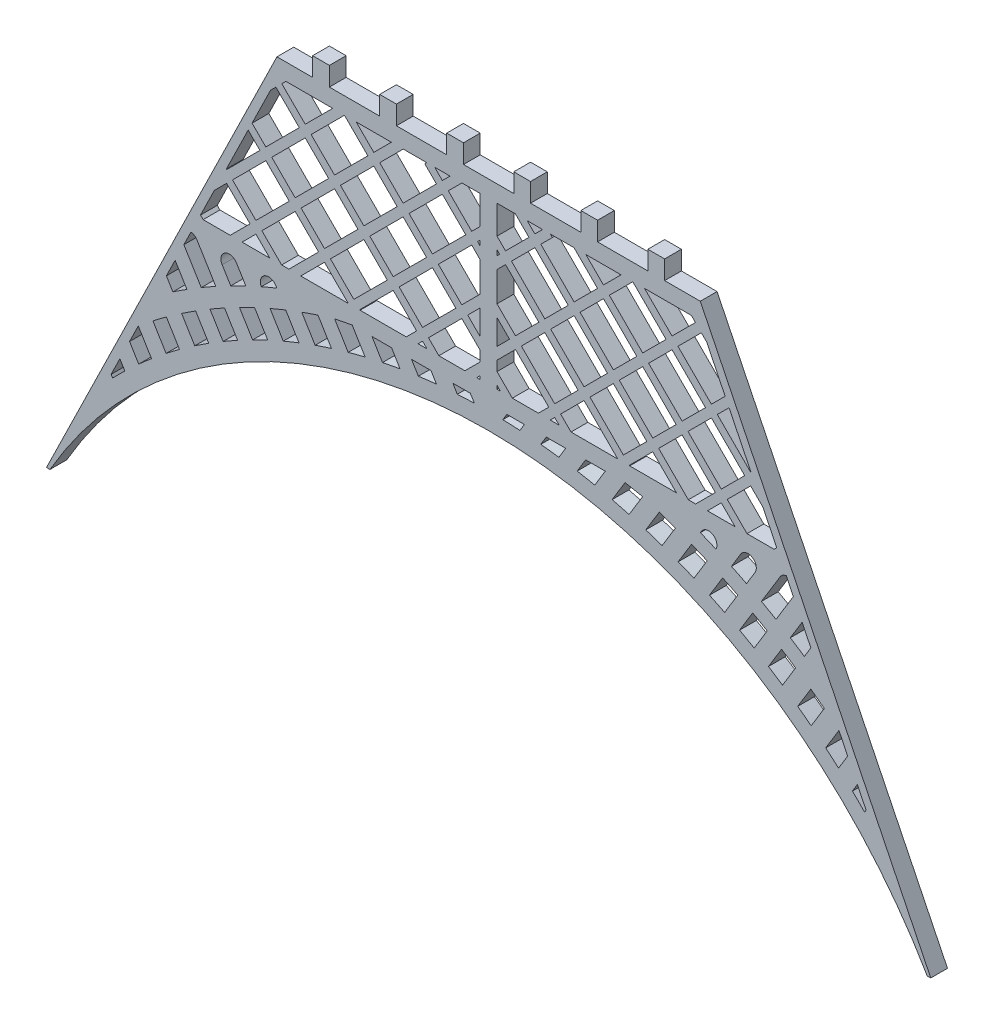
SolidWorks part; units mm, degrees
ref_plane "Front Plane" through (0, 0, 0) normal (0, 0, 1) x (1, 0, 0)
ref_plane "Top Plane" through (0, 0, 0) normal (0, 1, 0) x (1, 0, 0)
ref_plane "Right Plane" through (0, 0, 0) normal (1, 0, 0) x (0, 0, -1)
sketch "Sketch1" plane through (0, 0, 0) normal (0, 0, 1) x (1, 0, 0)
  line L1193 (183.6182, 220.7026) -> (187.8075, 224.8919)
  line L1194 (187.8075, 224.8919) -> (181.8448, 230.8547)
  line L1195 (181.8448, 230.8547) -> (180.3157, 229.3256)
  line L1196 (180.3157, 229.3256) -> (180.3157, 224.005)
  line L1197 (180.3157, 224.005) -> (183.6182, 220.7026)
  line L1198 (181.8448, 232.976) -> (186.0341, 237.1653)
  line L1199 (186.0341, 237.1653) -> (183.597, 239.6025)
  line L1200 (183.597, 239.6025) -> (180.3157, 239.6025)
  line L1201 (180.3157, 239.6025) -> (180.3157, 234.505)
  line L1202 (180.3157, 234.505) -> (181.8448, 232.976)
  line L1203 (180.9402, 210.7592) -> (180.3157, 211.3837)
  line L1204 (180.3157, 211.3837) -> (180.3157, 210.7592)
  line L1205 (180.3157, 210.7592) -> (180.9402, 210.7592)
  line L1206 (183.0615, 210.7592) -> (187.7216, 210.7592)
  line L1207 (187.7216, 210.7592) -> (189.5809, 212.6185)
  line L1208 (189.5809, 212.6185) -> (183.6182, 218.5813)
  line L1209 (183.6182, 218.5813) -> (180.3157, 215.2788)
  line L1210 (180.3157, 215.2788) -> (180.3157, 213.505)
  line L1211 (180.3157, 213.505) -> (183.0615, 210.7592)
  line L1212 (180.7841, 231.9153) -> (180.3157, 232.3837)
  line L1213 (180.3157, 232.3837) -> (180.3157, 231.4469)
  line L1214 (180.3157, 231.4469) -> (180.7841, 231.9153)
  line L1215 (182.5575, 219.6419) -> (180.3157, 221.8837)
  line L1216 (180.3157, 221.8837) -> (180.3157, 217.4002)
  line L1217 (180.3157, 217.4002) -> (182.5575, 219.6419)
  line L1218 (200.4288, 235.3919) -> (206.3916, 229.4292)
  line L1219 (206.3916, 229.4292) -> (210.5809, 233.6185)
  line L1220 (210.5809, 233.6185) -> (204.6182, 239.5813)
  line L1221 (204.6182, 239.5813) -> (200.4288, 235.3919)
  line L1222 (199.3682, 236.4526) -> (196.2183, 239.6025)
  line L1223 (196.2183, 239.6025) -> (202.5181, 239.6025)
  line L1224 (202.5181, 239.6025) -> (199.3682, 236.4526)
  line L1225 (195.1788, 230.1419) -> (201.1416, 224.1792)
  line L1226 (201.1416, 224.1792) -> (205.3309, 228.3685)
  line L1227 (205.3309, 228.3685) -> (199.3682, 234.3313)
  line L1228 (199.3682, 234.3313) -> (195.1788, 230.1419)
  line L1229 (198.3075, 235.3919) -> (194.1182, 231.2026)
  line L1230 (194.1182, 231.2026) -> (188.1554, 237.1653)
  line L1231 (188.1554, 237.1653) -> (190.241, 239.2509)
  line L1232 (190.241, 239.2509) -> (189.8895, 239.6025)
  line L1233 (189.8895, 239.6025) -> (194.097, 239.6025)
  line L1234 (194.097, 239.6025) -> (198.3075, 235.3919)
  line L1235 (187.0948, 236.1047) -> (182.9054, 231.9153)
  line L1236 (182.9054, 231.9153) -> (188.8682, 225.9526)
  line L1237 (188.8682, 225.9526) -> (193.0575, 230.1419)
  line L1238 (193.0575, 230.1419) -> (187.0948, 236.1047)
  line L1239 (189.9288, 224.8919) -> (195.8916, 218.9292)
  line L1240 (195.8916, 218.9292) -> (200.0809, 223.1185)
  line L1241 (200.0809, 223.1185) -> (194.1182, 229.0813)
  line L1242 (194.1182, 229.0813) -> (189.9288, 224.8919)
  line L1243 (215.8309, 238.8685) -> (215.097, 239.6025)
  line L1244 (215.097, 239.6025) -> (206.7183, 239.6025)
  line L1245 (206.7183, 239.6025) -> (211.6416, 234.6792)
  line L1246 (211.6416, 234.6792) -> (215.8309, 238.8685)
  line L1247 (207.4522, 228.3685) -> (213.4385, 222.3822)
  line L1248 (213.4385, 222.3822) -> (217.6279, 226.5716)
  line L1249 (217.6279, 226.5716) -> (211.6416, 232.5579)
  line L1250 (211.6416, 232.5579) -> (207.4522, 228.3685)
  line L1251 (202.2022, 223.1185) -> (208.1885, 217.1322)
  line L1252 (208.1885, 217.1322) -> (212.3779, 221.3216)
  line L1253 (212.3779, 221.3216) -> (206.3916, 227.3079)
  line L1254 (206.3916, 227.3079) -> (202.2022, 223.1185)
  line L1255 (196.9522, 217.8685) -> (202.9385, 211.8822)
  line L1256 (202.9385, 211.8822) -> (207.1279, 216.0716)
  line L1257 (207.1279, 216.0716) -> (201.1416, 222.0579)
  line L1258 (201.1416, 222.0579) -> (196.9522, 217.8685)
  line L1259 (188.8682, 223.8313) -> (184.6788, 219.6419)
  line L1260 (184.6788, 219.6419) -> (190.6416, 213.6792)
  line L1261 (190.6416, 213.6792) -> (194.8309, 217.8685)
  line L1262 (194.8309, 217.8685) -> (188.8682, 223.8313)
  line L1263 (193.5615, 210.7592) -> (201.8155, 210.7592)
  line L1264 (201.8155, 210.7592) -> (201.8779, 210.8216)
  line L1265 (201.8779, 210.8216) -> (195.8916, 216.8079)
  line L1266 (195.8916, 216.8079) -> (191.7022, 212.6185)
  line L1267 (191.7022, 212.6185) -> (193.5615, 210.7592)
  line L1268 (189.8429, 210.7592) -> (191.4402, 210.7592)
  line L1269 (191.4402, 210.7592) -> (190.6416, 211.5579)
  line L1270 (190.6416, 211.5579) -> (189.8429, 210.7592)
  line L1271 (187.0948, 238.226) -> (185.7183, 239.6025)
  line L1272 (185.7183, 239.6025) -> (188.4713, 239.6025)
  line L1273 (188.4713, 239.6025) -> (187.0948, 238.226)
  line L1274 (218.6885, 225.5109) -> (214.4992, 221.3216)
  line L1275 (214.4992, 221.3216) -> (220.4619, 215.3588)
  line L1276 (220.4619, 215.3588) -> (224.6513, 219.5482)
  line L1277 (224.6513, 219.5482) -> (218.6885, 225.5109)
  line L1278 (213.4385, 220.2609) -> (209.2492, 216.0716)
  line L1279 (209.2492, 216.0716) -> (214.5615, 210.7592)
  line L1280 (214.5615, 210.7592) -> (215.8623, 210.7592)
  line L1281 (215.8623, 210.7592) -> (219.4013, 214.2982)
  line L1282 (219.4013, 214.2982) -> (213.4385, 220.2609)
  line L1283 (217.9836, 210.7592) -> (222.9402, 210.7592)
  line L1284 (222.9402, 210.7592) -> (220.4619, 213.2375)
  line L1285 (220.4619, 213.2375) -> (217.9836, 210.7592)
  line L1286 (204.0615, 210.7592) -> (212.4402, 210.7592)
  line L1287 (212.4402, 210.7592) -> (208.1885, 215.0109)
  line L1288 (208.1885, 215.0109) -> (203.9992, 210.8216)
  line L1289 (203.9992, 210.8216) -> (204.0615, 210.7592)
  line L1290 (206.3818, 207.1538) -> (203.9493, 203.1685)
  line L1291 (200.9169, 203.9585) -> (203.2366, 207.7592)
  line L1292 (203.2366, 207.7592) -> (206.3818, 207.1538)
  line L1293 (199.7013, 207.7592) -> (197.8081, 204.6574)
  line L1294 (194.6573, 205.2536) -> (196.1866, 207.7592)
  line L1295 (196.1866, 207.7592) -> (199.7013, 207.7592)
  line L1296 (185.2265, 207.7592) -> (184.4181, 206.4348)
  line L1297 (181.3595, 206.5679) -> (182.0866, 207.7592)
  line L1298 (182.0866, 207.7592) -> (185.2265, 207.7592)
  line L1299 (212.2588, 205.232) -> (209.8641, 201.3086)
  line L1300 (206.943, 202.2809) -> (209.355, 206.2328)
  line L1301 (217.9315, 202.9754) -> (215.5634, 199.0955)
  line L1302 (212.7485, 200.242) -> (215.1285, 204.1415)
  line L1303 (223.4062, 200.3944) -> (221.0545, 196.5415)
  line L1304 (218.3427, 197.8568) -> (220.7013, 201.7212)
  line L1305 (228.6869, 197.4956) -> (226.3422, 193.654)
  line L1306 (223.7314, 195.1349) -> (226.0784, 198.9802)
  line L1307 (233.7605, 194.2914) -> (231.4135, 190.4461)
  line L1308 (228.9029, 192.0911) -> (231.2476, 195.9326)
  line L1309 (238.9003, 190.5743) -> (236.5408, 186.7085)
  line L1310 (234.1364, 188.5275) -> (236.4887, 192.3815)
  line L1311 (243.0812, 185.286) -> (241.4409, 182.5987)
  line L1312 (239.145, 184.5954) -> (241.5153, 188.4789)
  line L1313 (241.5153, 188.4789) -> (241.5207, 188.4745)
  line L1314 (241.5207, 188.4745) -> (243.0812, 185.286)
  line L1315 (233.3591, 205.1506) -> (230.25, 200.0566)
  line L1316 (227.6429, 201.5435) -> (230.9981, 207.0407)
  line L1317 (232.0883, 207.7471) -> (233.3591, 205.1506)
  line L1318 (222.273, 204.2962) -> (223.9481, 207.0407)
  line L1319 (226.5088, 205.4778) -> (224.9736, 202.9624)
  line L1320 (216.8981, 207.0407) -> (216.7134, 206.7382)
  line L1321 (188.1463, 206.1367) -> (189.1366, 207.7592)
  line L1322 (189.1366, 207.7592) -> (192.6145, 207.7592)
  line L1323 (192.6145, 207.7592) -> (191.391, 205.7547)
  line L1324 (221.151, 230.0948) -> (218.6885, 227.6322)
  line L1325 (218.6885, 227.6322) -> (212.7022, 233.6185)
  line L1326 (212.7022, 233.6185) -> (216.8916, 237.8079)
  line L1327 (216.8916, 237.8079) -> (217.8406, 236.8588)
  line L1328 (217.8406, 236.8588) -> (221.151, 230.0948)
  line L1329 (225.7668, 220.6637) -> (225.7119, 220.6088)
  line L1330 (225.7119, 220.6088) -> (219.7492, 226.5716)
  line L1331 (219.7492, 226.5716) -> (221.8481, 228.6705)
  line L1332 (221.8481, 228.6705) -> (225.7668, 220.6637)
  line L1333 (230.3825, 211.2326) -> (229.9091, 210.7592)
  line L1334 (229.9091, 210.7592) -> (225.0615, 210.7592)
  line L1335 (225.0615, 210.7592) -> (221.5226, 214.2982)
  line L1336 (221.5226, 214.2982) -> (225.7119, 218.4875)
  line L1337 (225.7119, 218.4875) -> (227.9053, 216.2942)
  line L1338 (227.9053, 216.2942) -> (230.3825, 211.2326)
  line L1339 (236.4873, 198.759) -> (234.9232, 201.9548)
  line L1340 (234.9232, 201.9548) -> (232.8107, 198.4936)
  line L1341 (235.325, 196.8548) -> (236.4873, 198.759)
  line L1342 (246.3781, 178.5495) -> (244.814, 181.7454)
  line L1343 (244.814, 181.7454) -> (243.9231, 180.2856)
  line L1344 (246.1067, 178.1049) -> (246.3781, 178.5495)
  line L1345 (174.0133, 220.7026) -> (169.824, 224.8919)
  line L1346 (169.824, 224.8919) -> (175.7867, 230.8547)
  line L1347 (175.7867, 230.8547) -> (177.3157, 229.3256)
  line L1348 (177.3157, 229.3256) -> (177.3157, 224.005)
  line L1349 (177.3157, 224.005) -> (174.0133, 220.7026)
  line L1350 (175.7867, 232.976) -> (171.5974, 237.1653)
  line L1351 (171.5974, 237.1653) -> (174.0345, 239.6025)
  line L1352 (174.0345, 239.6025) -> (177.3157, 239.6025)
  line L1353 (177.3157, 239.6025) -> (177.3157, 234.505)
  line L1354 (177.3157, 234.505) -> (175.7867, 232.976)
  line L1355 (176.6913, 210.7592) -> (177.3157, 211.3837)
  line L1356 (177.3157, 211.3837) -> (177.3157, 210.7592)
  line L1357 (177.3157, 210.7592) -> (176.6913, 210.7592)
  line L1358 (174.5699, 210.7592) -> (169.9099, 210.7592)
  line L1359 (169.9099, 210.7592) -> (168.0506, 212.6185)
  line L1360 (168.0506, 212.6185) -> (174.0133, 218.5813)
  line L1361 (174.0133, 218.5813) -> (177.3157, 215.2788)
  line L1362 (177.3157, 215.2788) -> (177.3157, 213.505)
  line L1363 (177.3157, 213.505) -> (174.5699, 210.7592)
  line L1364 (176.8474, 231.9153) -> (177.3157, 232.3837)
  line L1365 (177.3157, 232.3837) -> (177.3157, 231.4469)
  line L1366 (177.3157, 231.4469) -> (176.8474, 231.9153)
  line L1367 (175.074, 219.6419) -> (177.3157, 221.8837)
  line L1368 (177.3157, 221.8837) -> (177.3157, 217.4002)
  line L1369 (177.3157, 217.4002) -> (175.074, 219.6419)
  line L1370 (157.2026, 235.3919) -> (151.2399, 229.4292)
  line L1371 (151.2399, 229.4292) -> (147.0506, 233.6185)
  line L1372 (147.0506, 233.6185) -> (153.0133, 239.5813)
  line L1373 (153.0133, 239.5813) -> (157.2026, 235.3919)
  line L1374 (158.2633, 236.4526) -> (161.4132, 239.6025)
  line L1375 (161.4132, 239.6025) -> (155.1134, 239.6025)
  line L1376 (155.1134, 239.6025) -> (158.2633, 236.4526)
  line L1377 (162.4526, 230.1419) -> (156.4899, 224.1792)
  line L1378 (156.4899, 224.1792) -> (152.3006, 228.3685)
  line L1379 (152.3006, 228.3685) -> (158.2633, 234.3313)
  line L1380 (158.2633, 234.3313) -> (162.4526, 230.1419)
  line L1381 (159.324, 235.3919) -> (163.5133, 231.2026)
  line L1382 (163.5133, 231.2026) -> (169.476, 237.1653)
  line L1383 (169.476, 237.1653) -> (167.3904, 239.2509)
  line L1384 (167.3904, 239.2509) -> (167.742, 239.6025)
  line L1385 (167.742, 239.6025) -> (163.5345, 239.6025)
  line L1386 (163.5345, 239.6025) -> (159.324, 235.3919)
  line L1387 (170.5367, 236.1047) -> (174.726, 231.9153)
  line L1388 (174.726, 231.9153) -> (168.7633, 225.9526)
  line L1389 (168.7633, 225.9526) -> (164.574, 230.1419)
  line L1390 (164.574, 230.1419) -> (170.5367, 236.1047)
  line L1391 (167.7026, 224.8919) -> (161.7399, 218.9292)
  line L1392 (161.7399, 218.9292) -> (157.5506, 223.1185)
  line L1393 (157.5506, 223.1185) -> (163.5133, 229.0813)
  line L1394 (163.5133, 229.0813) -> (167.7026, 224.8919)
  line L1395 (141.8006, 238.8685) -> (142.5345, 239.6025)
  line L1396 (142.5345, 239.6025) -> (150.9132, 239.6025)
  line L1397 (150.9132, 239.6025) -> (145.9899, 234.6792)
  line L1398 (145.9899, 234.6792) -> (141.8006, 238.8685)
  line L1399 (150.1792, 228.3685) -> (144.1929, 222.3822)
  line L1400 (144.1929, 222.3822) -> (140.0036, 226.5716)
  line L1401 (140.0036, 226.5716) -> (145.9899, 232.5579)
  line L1402 (145.9899, 232.5579) -> (150.1792, 228.3685)
  line L1403 (155.4292, 223.1185) -> (149.4429, 217.1322)
  line L1404 (149.4429, 217.1322) -> (145.2536, 221.3216)
  line L1405 (145.2536, 221.3216) -> (151.2399, 227.3079)
  line L1406 (151.2399, 227.3079) -> (155.4292, 223.1185)
  line L1407 (160.6792, 217.8685) -> (154.6929, 211.8822)
  line L1408 (154.6929, 211.8822) -> (150.5036, 216.0716)
  line L1409 (150.5036, 216.0716) -> (156.4899, 222.0579)
  line L1410 (156.4899, 222.0579) -> (160.6792, 217.8685)
  line L1411 (168.7633, 223.8313) -> (172.9526, 219.6419)
  line L1412 (172.9526, 219.6419) -> (166.9899, 213.6792)
  line L1413 (166.9899, 213.6792) -> (162.8006, 217.8685)
  line L1414 (162.8006, 217.8685) -> (168.7633, 223.8313)
  line L1415 (164.0699, 210.7592) -> (155.8159, 210.7592)
  line L1416 (155.8159, 210.7592) -> (155.7536, 210.8216)
  line L1417 (155.7536, 210.8216) -> (161.7399, 216.8079)
  line L1418 (161.7399, 216.8079) -> (165.9292, 212.6185)
  line L1419 (165.9292, 212.6185) -> (164.0699, 210.7592)
  line L1420 (167.7885, 210.7592) -> (166.1913, 210.7592)
  line L1421 (166.1913, 210.7592) -> (166.9899, 211.5579)
  line L1422 (166.9899, 211.5579) -> (167.7885, 210.7592)
  line L1423 (170.5367, 238.226) -> (171.9132, 239.6025)
  line L1424 (171.9132, 239.6025) -> (169.1602, 239.6025)
  line L1425 (169.1602, 239.6025) -> (170.5367, 238.226)
  line L1426 (138.9429, 225.5109) -> (143.1323, 221.3216)
  line L1427 (143.1323, 221.3216) -> (137.1695, 215.3588)
  line L1428 (137.1695, 215.3588) -> (132.9802, 219.5482)
  line L1429 (132.9802, 219.5482) -> (138.9429, 225.5109)
  line L1430 (144.1929, 220.2609) -> (148.3823, 216.0716)
  line L1431 (148.3823, 216.0716) -> (143.0699, 210.7592)
  line L1432 (143.0699, 210.7592) -> (141.7691, 210.7592)
  line L1433 (141.7691, 210.7592) -> (138.2302, 214.2982)
  line L1434 (138.2302, 214.2982) -> (144.1929, 220.2609)
  line L1435 (139.6478, 210.7592) -> (134.6913, 210.7592)
  line L1436 (134.6913, 210.7592) -> (137.1695, 213.2375)
  line L1437 (137.1695, 213.2375) -> (139.6478, 210.7592)
  line L1438 (153.5699, 210.7592) -> (145.1913, 210.7592)
  line L1439 (145.1913, 210.7592) -> (149.4429, 215.0109)
  line L1440 (149.4429, 215.0109) -> (153.6323, 210.8216)
  line L1441 (153.6323, 210.8216) -> (153.5699, 210.7592)
  line L1442 (151.2497, 207.1538) -> (153.6821, 203.1685)
  line L1443 (156.7146, 203.9585) -> (154.3948, 207.7592)
  line L1444 (154.3948, 207.7592) -> (151.2497, 207.1538)
  line L1445 (157.9302, 207.7592) -> (159.8234, 204.6574)
  line L1446 (162.9742, 205.2536) -> (161.4448, 207.7592)
  line L1447 (161.4448, 207.7592) -> (157.9302, 207.7592)
  line L1448 (172.405, 207.7592) -> (173.2133, 206.4348)
  line L1449 (176.2719, 206.5679) -> (175.5448, 207.7592)
  line L1450 (175.5448, 207.7592) -> (172.405, 207.7592)
  line L1451 (145.3727, 205.232) -> (147.7673, 201.3086)
  line L1452 (150.6885, 202.2809) -> (148.2765, 206.2328)
  line L1453 (139.7, 202.9754) -> (142.0681, 199.0955)
  line L1454 (144.8829, 200.242) -> (142.5029, 204.1415)
  line L1455 (134.2253, 200.3944) -> (136.5769, 196.5415)
  line L1456 (139.2888, 197.8568) -> (136.9302, 201.7212)
  line L1457 (128.9446, 197.4956) -> (131.2893, 193.654)
  line L1458 (133.9001, 195.1349) -> (131.5531, 198.9802)
  line L1459 (123.8709, 194.2914) -> (126.2179, 190.4461)
  line L1460 (128.7286, 192.0911) -> (126.3839, 195.9326)
  line L1461 (118.7312, 190.5743) -> (121.0906, 186.7085)
  line L1462 (123.495, 188.5275) -> (121.1428, 192.3815)
  line L1463 (114.5503, 185.286) -> (116.1905, 182.5987)
  line L1464 (118.4865, 184.5954) -> (116.1162, 188.4789)
  line L1465 (116.1162, 188.4789) -> (116.1108, 188.4745)
  line L1466 (116.1108, 188.4745) -> (114.5503, 185.286)
  line L1467 (124.2724, 205.1506) -> (127.3815, 200.0566)
  line L1468 (129.9886, 201.5435) -> (126.6334, 207.0407)
  line L1469 (125.5431, 207.7471) -> (124.2724, 205.1506)
  line L1470 (135.3585, 204.2962) -> (133.6834, 207.0407)
  line L1471 (131.1227, 205.4778) -> (132.6579, 202.9624)
  line L1472 (140.7334, 207.0407) -> (140.918, 206.7382)
  line L1473 (169.4851, 206.1367) -> (168.4948, 207.7592)
  line L1474 (168.4948, 207.7592) -> (165.017, 207.7592)
  line L1475 (165.017, 207.7592) -> (166.2404, 205.7547)
  line L1476 (136.4804, 230.0948) -> (138.9429, 227.6322)
  line L1477 (138.9429, 227.6322) -> (144.9292, 233.6185)
  line L1478 (144.9292, 233.6185) -> (140.7399, 237.8079)
  line L1479 (140.7399, 237.8079) -> (139.7909, 236.8588)
  line L1480 (139.7909, 236.8588) -> (136.4804, 230.0948)
  line L1481 (131.8647, 220.6637) -> (131.9195, 220.6088)
  line L1482 (131.9195, 220.6088) -> (137.8823, 226.5716)
  line L1483 (137.8823, 226.5716) -> (135.7834, 228.6705)
  line L1484 (135.7834, 228.6705) -> (131.8647, 220.6637)
  line L1485 (127.249, 211.2326) -> (127.7224, 210.7592)
  line L1486 (127.7224, 210.7592) -> (132.5699, 210.7592)
  line L1487 (132.5699, 210.7592) -> (136.1089, 214.2982)
  line L1488 (136.1089, 214.2982) -> (131.9195, 218.4875)
  line L1489 (131.9195, 218.4875) -> (129.7262, 216.2942)
  line L1490 (129.7262, 216.2942) -> (127.249, 211.2326)
  line L1491 (121.1442, 198.759) -> (122.7083, 201.9548)
  line L1492 (122.7083, 201.9548) -> (124.8208, 198.4936)
  line L1493 (122.3064, 196.8548) -> (121.1442, 198.759)
  line L1494 (111.2534, 178.5495) -> (112.8174, 181.7454)
  line L1495 (112.8174, 181.7454) -> (113.7084, 180.2856)
  line L1496 (111.5247, 178.1049) -> (111.2534, 178.5495)
  line L1497 (178.8157, 242.6025) -> (174.3157, 242.6025)
  line L1498 (174.3157, 242.6025) -> (174.3157, 245.9686)
  line L1499 (174.3157, 245.9686) -> (171.3157, 245.9686)
  line L1500 (171.3157, 245.9686) -> (171.3157, 242.6025)
  line L1501 (171.3157, 242.6025) -> (162.3157, 242.6025)
  line L1502 (162.3157, 242.6025) -> (162.3157, 245.9686)
  line L1503 (162.3157, 245.9686) -> (159.3157, 245.9686)
  line L1504 (159.3157, 245.9686) -> (159.3157, 242.6025)
  line L1505 (159.3157, 242.6025) -> (150.3157, 242.6025)
  line L1506 (150.3157, 242.6025) -> (150.3157, 245.9686)
  line L1507 (150.3157, 245.9686) -> (147.3157, 245.9686)
  line L1508 (147.3157, 245.9686) -> (147.3157, 242.6025)
  line L1509 (147.3157, 242.6025) -> (140.9319, 242.6025)
  line L1510 (140.9319, 242.6025) -> (99.6856, 158.3259)
  line L1511 (99.6856, 158.3259) -> (100.3122, 158.3259)
  line L1512 (257.3193, 158.3259) -> (257.9459, 158.3259)
  line L1513 (257.9459, 158.3259) -> (216.6996, 242.6025)
  line L1514 (216.6996, 242.6025) -> (210.3157, 242.6025)
  line L1515 (210.3157, 242.6025) -> (210.3157, 245.9686)
  line L1516 (210.3157, 245.9686) -> (207.3157, 245.9686)
  line L1517 (207.3157, 245.9686) -> (207.3157, 242.6025)
  line L1518 (207.3157, 242.6025) -> (198.3157, 242.6025)
  line L1519 (198.3157, 242.6025) -> (198.3157, 245.9686)
  line L1520 (198.3157, 245.9686) -> (195.3157, 245.9686)
  line L1521 (195.3157, 245.9686) -> (195.3157, 242.6025)
  line L1522 (195.3157, 242.6025) -> (186.3157, 242.6025)
  line L1523 (186.3157, 242.6025) -> (186.3157, 245.9686)
  line L1524 (186.3157, 245.9686) -> (183.3157, 245.9686)
  line L1525 (183.3157, 245.9686) -> (183.3157, 242.6025)
  line L1526 (183.3157, 242.6025) -> (178.8157, 242.6025)
  arc A67 (203.9493, 203.1685) -> (200.9169, 203.9585) centre (178.8157, 112.9069) ccw
  arc A68 (197.8081, 204.6574) -> (194.6573, 205.2536) centre (178.8157, 112.9069) ccw
  arc A69 (184.4181, 206.4348) -> (181.3595, 206.5679) centre (178.8157, 112.9069) ccw
  arc A70 (209.8641, 201.3086) -> (206.943, 202.2809) centre (178.8157, 112.9069) ccw
  arc A71 (212.2588, 205.232) -> (209.355, 206.2328) centre (178.8157, 112.9069) ccw
  arc A72 (215.5634, 199.0955) -> (212.7485, 200.242) centre (178.8157, 112.9069) ccw
  arc A73 (217.9315, 202.9754) -> (215.1285, 204.1415) centre (178.8157, 112.9069) ccw
  arc A74 (221.0545, 196.5415) -> (218.3427, 197.8568) centre (178.8157, 112.9069) ccw
  arc A75 (223.4062, 200.3944) -> (220.7013, 201.7212) centre (178.8157, 112.9069) ccw
  arc A76 (226.3422, 193.654) -> (223.7314, 195.1349) centre (178.8157, 112.9069) ccw
  arc A77 (228.6869, 197.4956) -> (226.0784, 198.9802) centre (178.8157, 112.9069) ccw
  arc A78 (231.4135, 190.4461) -> (228.9029, 192.0911) centre (178.8157, 112.9069) ccw
  arc A79 (233.7605, 194.2914) -> (231.2476, 195.9326) centre (178.8157, 112.9069) ccw
  arc A80 (236.5408, 186.7085) -> (234.1364, 188.5275) centre (178.8157, 112.9069) ccw
  arc A81 (238.9003, 190.5743) -> (236.4887, 192.3815) centre (178.8157, 112.9069) ccw
  arc A82 (241.4409, 182.5987) -> (239.145, 184.5954) centre (178.8157, 112.9069) ccw
  arc A83 (230.25, 200.0566) -> (227.6429, 201.5435) centre (178.8157, 112.9069) ccw
  arc A84 (232.0883, 207.7471) -> (230.9981, 207.0407) centre (232.2784, 206.2592) ccw
  arc A85 (226.5088, 205.4778) -> (223.9481, 207.0407) centre (225.2284, 206.2592) ccw
  arc A86 (224.9736, 202.9624) -> (222.273, 204.2962) centre (178.8157, 112.9069) ccw
  arc A87 (219.5062, 205.5613) -> (216.7134, 206.7382) centre (178.8157, 112.9069) ccw
  arc A88 (219.5062, 205.5613) -> (216.8981, 207.0407) centre (218.1784, 206.2592) ccw
  arc A89 (191.391, 205.7547) -> (188.1463, 206.1367) centre (178.8157, 112.9069) ccw
  arc A90 (235.325, 196.8548) -> (232.8107, 198.4936) centre (178.8157, 112.9069) ccw
  arc A91 (246.1067, 178.1049) -> (243.9231, 180.2856) centre (178.8157, 112.9069) ccw
  arc A92 (156.7146, 203.9585) -> (153.6821, 203.1685) centre (178.8157, 112.9069) ccw
  arc A93 (162.9742, 205.2536) -> (159.8234, 204.6574) centre (178.8157, 112.9069) ccw
  arc A94 (176.2719, 206.5679) -> (173.2133, 206.4348) centre (178.8157, 112.9069) ccw
  arc A95 (150.6885, 202.2809) -> (147.7673, 201.3086) centre (178.8157, 112.9069) ccw
  arc A96 (148.2765, 206.2328) -> (145.3727, 205.232) centre (178.8157, 112.9069) ccw
  arc A97 (144.8829, 200.242) -> (142.0681, 199.0955) centre (178.8157, 112.9069) ccw
  arc A98 (142.5029, 204.1415) -> (139.7, 202.9754) centre (178.8157, 112.9069) ccw
  arc A99 (139.2888, 197.8568) -> (136.5769, 196.5415) centre (178.8157, 112.9069) ccw
  arc A100 (136.9302, 201.7212) -> (134.2253, 200.3944) centre (178.8157, 112.9069) ccw
  arc A101 (133.9001, 195.1349) -> (131.2893, 193.654) centre (178.8157, 112.9069) ccw
  arc A102 (131.5531, 198.9802) -> (128.9446, 197.4956) centre (178.8157, 112.9069) ccw
  arc A103 (128.7286, 192.0911) -> (126.2179, 190.4461) centre (178.8157, 112.9069) ccw
  arc A104 (126.3839, 195.9326) -> (123.8709, 194.2914) centre (178.8157, 112.9069) ccw
  arc A105 (123.495, 188.5275) -> (121.0906, 186.7085) centre (178.8157, 112.9069) ccw
  arc A106 (121.1428, 192.3815) -> (118.7312, 190.5743) centre (178.8157, 112.9069) ccw
  arc A107 (118.4865, 184.5954) -> (116.1905, 182.5987) centre (178.8157, 112.9069) ccw
  arc A108 (129.9886, 201.5435) -> (127.3815, 200.0566) centre (178.8157, 112.9069) ccw
  arc A109 (126.6334, 207.0407) -> (125.5431, 207.7471) centre (125.353, 206.2592) ccw
  arc A110 (133.6834, 207.0407) -> (131.1227, 205.4778) centre (132.403, 206.2592) ccw
  arc A111 (135.3585, 204.2962) -> (132.6579, 202.9624) centre (178.8157, 112.9069) ccw
  arc A112 (140.918, 206.7382) -> (138.1253, 205.5613) centre (178.8157, 112.9069) ccw
  arc A113 (140.7334, 207.0407) -> (138.1253, 205.5613) centre (139.453, 206.2592) ccw
  arc A114 (169.4851, 206.1367) -> (166.2404, 205.7547) centre (178.8157, 112.9069) ccw
  arc A115 (124.8208, 198.4936) -> (122.3064, 196.8548) centre (178.8157, 112.9069) ccw
  arc A116 (113.7084, 180.2856) -> (111.5247, 178.1049) centre (178.8157, 112.9069) ccw
  arc A117 (257.3193, 158.3259) -> (100.3122, 158.3259) centre (178.8157, 112.9069) ccw
extrude "Boss-Extrude1" add sketch "Sketch1" along normal blind 3
